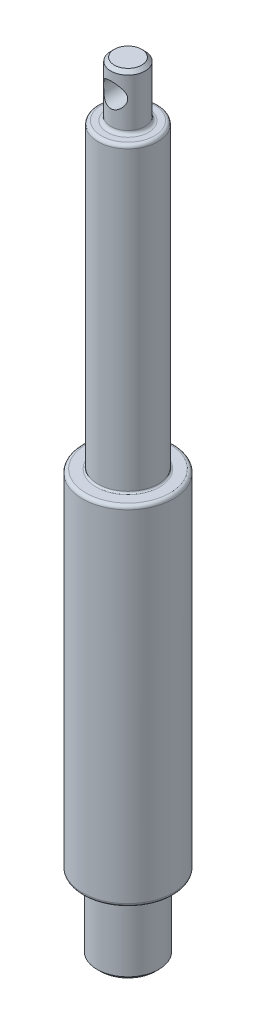
SolidWorks part; units mm, degrees
material "AISI 1010 Barra de acero laminada en caliente"
ref_plane "Alzado" through (0, 0, 0) normal (0, 0, 1) x (1, 0, 0)
ref_plane "Planta" through (0, 0, 0) normal (0, 1, 0) x (1, 0, 0)
ref_plane "Vista lateral" through (0, 0, 0) normal (1, 0, 0) x (0, 0, -1)
sketch "Croquis1" plane through (0, 0, 0) normal (1, 0, 0) x (0, 0, -1)
  line L0 (0, 227) -> (0, 0)
  line L1 (0, 0) -> (9, 0)
  line L2 (9, 0) -> (9, 21.5)
  line L3 (9, 21.5) -> (13.25, 21.5)
  line L4 (13.25, 21.5) -> (13.25, 123)
  line L5 (13.25, 123) -> (8.75, 123)
  line L6 (8.75, 123) -> (8.75, 211)
  line L7 (5, 227) -> (0, 227)
  line L8 (8.75, 211) -> (5, 211)
  line L9 (5, 211) -> (5, 227)
  dimension "D1" = 9
  dimension "D2" = 13.25
  dimension "D3" = 21.5
  dimension "D4" = 123
  dimension "D5" = 227
  dimension "D6" = 211
  dimension "D7" = 8.75
  dimension "D8" = 5
revolve "Revolución1" add sketch "Croquis1" angle 360 about L0
sketch "Croquis3" plane through (0, 0, 0) normal (0, 0, 1) x (1, 0, 0)
  line L0 (0, 227) -> (0, 211) construction
  line L1 (5, 227) -> (-5, 227) construction
  line L2 (8.75, 211) -> (-8.75, 211) construction
  circle A0 centre (0, 220) radius 3.5
  dimension "D1" = 7
  dimension "D2" = 7
extrude "Cortar-Extruir1" cut sketch "Croquis3" against normal through all both and the other way through all
chamfer "Chaflán2" distance 1 angle 45 1 edges at (0, 227, 5)
fillet "Redondeo1" radius 1 4 edges at (0, 21.5, 9) (0, 123, 13.25) (0, 21.5, 13.25) (0, 211, 8.75)
fillet "Redondeo3" radius 1 1 edges at (0, 211, 5)
chamfer "Chaflán3" distance 1 angle 45 1 edges at (0, 0, 9)
sketch "Croquis4" plane through (0, 0, 0) normal (0, -1, 0) x (1, 0, 0)
  point P0 (0, 0)
hole_wizard "Taladro de margen para M121" positions "Croquis5" profile "Croquis6" hole size "M12" standard "DIN"
sketch "Croquis5" plane through (0, 0, 0) normal (0, -1, 0) x (-1, 0, 0)
  point P0 (0, 0)
sketch "Croquis6" plane through (0, 0, 0) normal (1, 0, 0) x (0, 0, -1)
  line L0 (0, 0) -> (0, 18.0794)
  line L1 (0, 18.0794) -> (5.125, 15)
  line L2 (5.125, 15) -> (5.125, 0)
  line L5 (5.125, 0) -> (0, 0)
  line L10 (0, 18.0794) -> (-5.125, 15) construction
  line L11 (0, -6.35) -> (0, 107.95) construction
  dimension "Diámetro de taladro" = 10.25
  dimension "Profundidad de taladro" = 15
  dimension "Ángulo de perforador" = 118
fillet "Redondeo4" radius 0.5 1 edges at (0, 123, 8.75)
